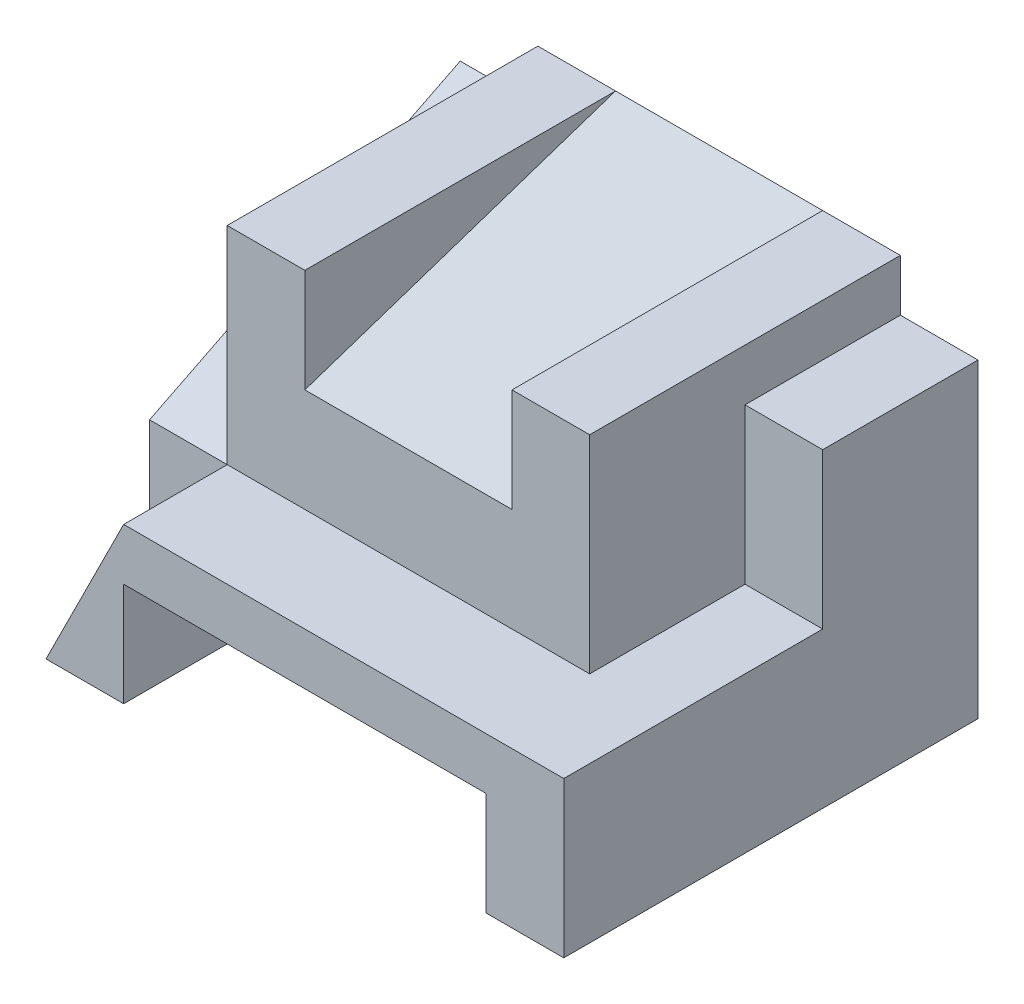
SolidWorks part; units mm, degrees
ref_plane "Alzado" through (0, 0, 0) normal (0, 0, 1) x (1, 0, 0)
ref_plane "Planta" through (0, 0, 0) normal (0, 1, 0) x (1, 0, 0)
ref_plane "Vista lateral" through (0, 0, 0) normal (1, 0, 0) x (0, 0, -1)
sketch "Croquis1" plane through (0, 0, 0) normal (0, 0, 1) x (1, 0, 0)
  line L0 (-3.5, 0) -> (3.5, 0) construction
  line L1 (-3.5, 0) -> (-5, 0)
  line L2 (-5, 0) -> (-5, 3)
  line L3 (-5, 3) -> (5, 3)
  line L4 (5, 3) -> (5, 0)
  line L5 (5, 0) -> (3.5, 0)
  line L6 (-3.5, 0) -> (-3.5, 2)
  line L7 (-3.5, 2) -> (3.5, 2)
  line L8 (3.5, 2) -> (3.5, 0)
  point P3 (0, 3)
  point P4 (0, 0)
  point P10 (3.5, 1)
  dimension "D1" = 7
  dimension "D2" = 3
  dimension "D3" = 2
  dimension "D4" = 10
extrude "Saliente-Extruir1" add sketch "Croquis1" against normal blind 8
sketch "Croquis2" plane through (0, 0, 0) normal (0, 0, 1) x (1, 0, 0)
  line L0 (-5, 0) -> (-3.5, 3)
  line L1 (5, 3) -> (-5, 3) construction
  line L2 (-3.5, 3) -> (-5, 3)
  line L3 (-5, 3) -> (-5, 0)
  point P5 (-3.5641, 3)
  dimension "D1" = 1.5
extrude "Cortar-Extruir2" cut sketch "Croquis2" against normal blind 2
ref_plane "Plano1" through (0, 0, -2) normal (0, 0, 1) x (1, 0, 0)
sketch "Croquis3" plane through (0, 0, -2) normal (0, 0, 1) x (1, 0, 0)
  line L0 (-3.5, 3) -> (-3.5, 7)
  line L1 (-3.5, 7) -> (3.5, 7)
  line L2 (3.5, 7) -> (3.5, 3)
  line L3 (5, 3) -> (-3.5, 3) construction
  line L4 (3.5, 3) -> (-3.5, 3)
  point P3 (0, 7)
  dimension "D1" = 4
extrude "Saliente-Extruir2" add sketch "Croquis3" against normal blind 6
sketch "Croquis4" plane through (0, 7, 0) normal (0, 1, 0) x (1, 0, 0)
  line L0 (-2, 8) -> (2, 8)
  line L1 (3.5, 8) -> (-3.5, 8) construction
  line L2 (2, 8) -> (2, 2)
  line L3 (-4.2187, 2) -> (4.2187, 2) construction
  line L4 (2, 2) -> (-2, 2)
  line L5 (-2, 2) -> (-2, 8)
  point P4 (0, 8)
  dimension "D1" = 4
extrude "Cortar-Extruir3" cut sketch "Croquis4" against normal blind 2
sketch "Croquis5" plane through (2, 0, 0) normal (-1, 0, 0) x (0, 0, 1)
  line L0 (-8, 7) -> (-2, 5)
  line L1 (-2, -4.2187) -> (-2, 4.2187) construction
  line L2 (-2, 5) -> (-8, 5)
  line L3 (-8, 7) -> (-8, 3) construction
  line L4 (-8, 5) -> (-8, 7)
extrude "Saliente-Extruir3" add sketch "Croquis5" along normal blind 4
sketch "Croquis6" plane through (-3.5, 0, 0) normal (-1, 0, 0) x (0, 0, 1)
  line L0 (-8, 6) -> (-2, 3)
  line L1 (-8, 7) -> (-8, 3) construction
  line L2 (-2, -4.2187) -> (-2, 4.2187) construction
  line L3 (-8, 3) -> (-2, 3) construction
  line L4 (-2, 3) -> (-8, 3)
  line L5 (-8, 3) -> (-8, 6)
  dimension "D1" = 1
extrude "Saliente-Extruir4" add sketch "Croquis6" along normal blind 1.5
sketch "Croquis7" plane through (0, 3, 0) normal (0, 1, 0) x (1, 0, 0)
  line L0 (3.5, 8) -> (5, 8)
  line L1 (5, 8) -> (5, 5)
  line L2 (5, 8) -> (5, 0) construction
  line L3 (5, 5) -> (3.5, 5)
  line L4 (3.5, 8) -> (3.5, 2) construction
  line L5 (3.5, 5) -> (3.5, 8)
  dimension "D1" = 3
extrude "Saliente-Extruir5" add sketch "Croquis7" along normal blind 3
